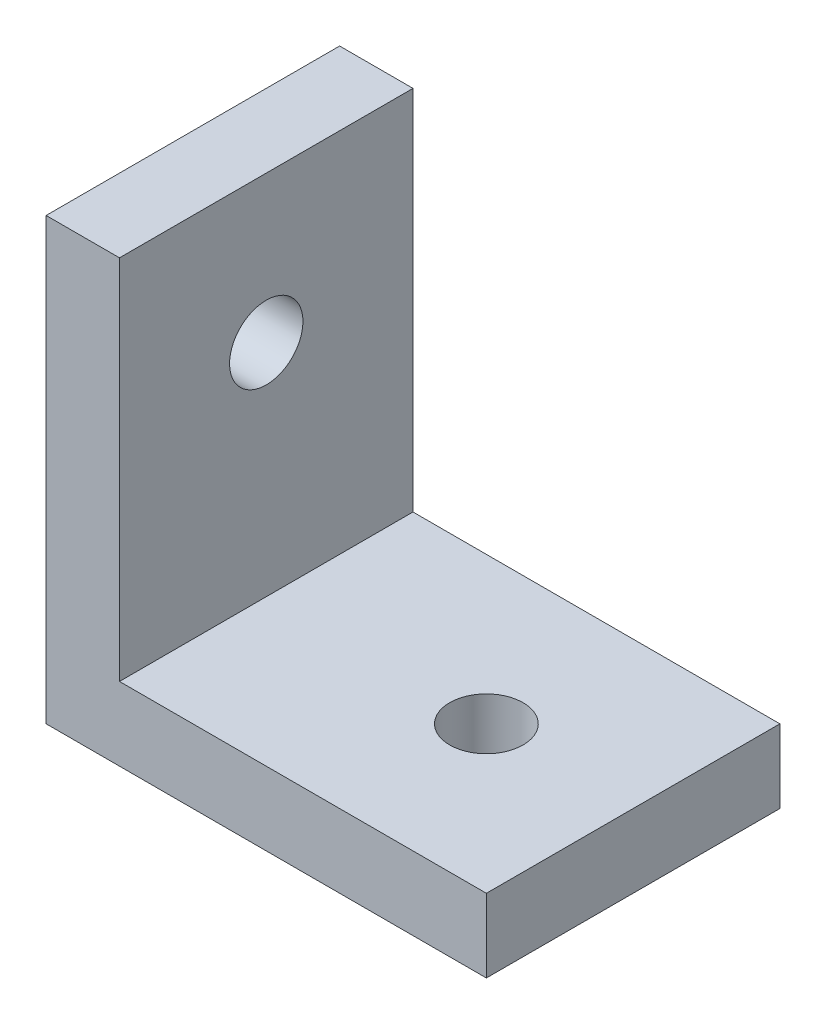
SolidWorks part; units mm, degrees
material "6061 Alloy"
ref_plane "Front Plane" through (0, 0, 0) normal (0, 0, 1) x (1, 0, 0)
ref_plane "Top Plane" through (0, 0, 0) normal (0, 1, 0) x (1, 0, 0)
ref_plane "Right Plane" through (0, 0, 0) normal (1, 0, 0) x (0, 0, -1)
sketch "Sketch1" plane through (0, 0, 0) normal (0, 0, 1) x (1, 0, 0)
  line L0 (0, 0) -> (0, -31.75)
  line L1 (0, -31.75) -> (31.75, -31.75)
  line L2 (-6.35, 0) -> (-6.35, -38.1)
  line L3 (-6.35, -38.1) -> (31.75, -38.1)
  line L4 (-6.35, 0) -> (0, 0)
  line L5 (31.75, -31.75) -> (31.75, -38.1)
  dimension "D2" = 38.1
  dimension "D3" = 38.1
  dimension "D1" = 6.35
extrude "Boss-Extrude1" add sketch "Sketch1" along normal blind 25.4
sketch "Sketch2" plane through (0, 0, 0) normal (1, 0, 0) x (0, 0, -1)
  line L0 (0, -31.75) -> (0, 0) construction
  line L1 (-25.4, 0) -> (0, 0) construction
  circle A0 centre (-12.7, -12.7) radius 3.175
  dimension "D1" = 6.35
  dimension "D2" = 12.7
  dimension "D3" = 12.7
extrude "Cut-Extrude1" cut sketch "Sketch2" against normal up to next
sketch "Sketch3" plane through (0, -31.75, 0) normal (0, 1, 0) x (1, 0, 0)
  line L0 (31.75, -25.4) -> (31.75, 0) construction
  line L1 (31.75, -25.4) -> (0, -25.4) construction
  circle A0 centre (19.05, -12.7) radius 3.175
  dimension "D1" = 6.35
  dimension "D2" = 12.7
  dimension "D3" = 12.7
extrude "Cut-Extrude2" cut sketch "Sketch3" against normal up to next
